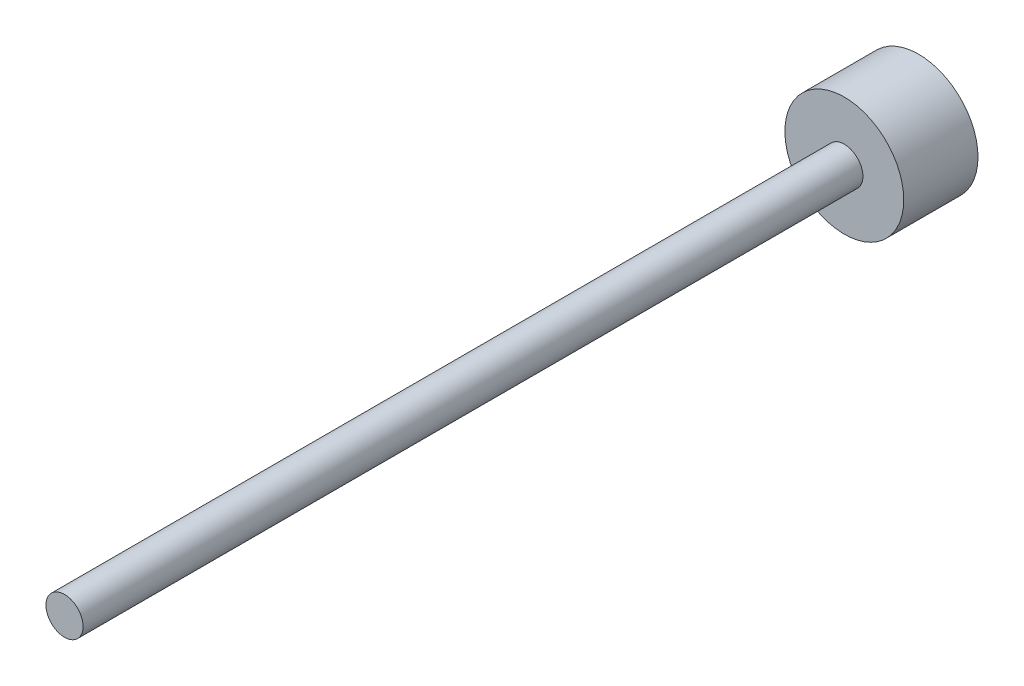
SolidWorks part; units mm, degrees
ref_plane "前视基准面" through (0, 0, 0) normal (0, 0, 1) x (1, 0, 0)
ref_plane "上视基准面" through (0, 0, 0) normal (0, 1, 0) x (1, 0, 0)
ref_plane "右视基准面" through (0, 0, 0) normal (1, 0, 0) x (0, 0, -1)
sketch "草图1" plane through (0, 0, 0) normal (0, 0, 1) x (1, 0, 0)
  circle A0 centre (0, 0) radius 8
extrude "凸台-拉伸1" add sketch "草图1" along normal blind 10
sketch "草图2" plane through (0, 0, 10) normal (0, 0, 1) x (1, 0, 0)
  circle A0 centre (0, 0) radius 2.5
extrude "凸台-拉伸2" add sketch "草图2" along normal blind 105
